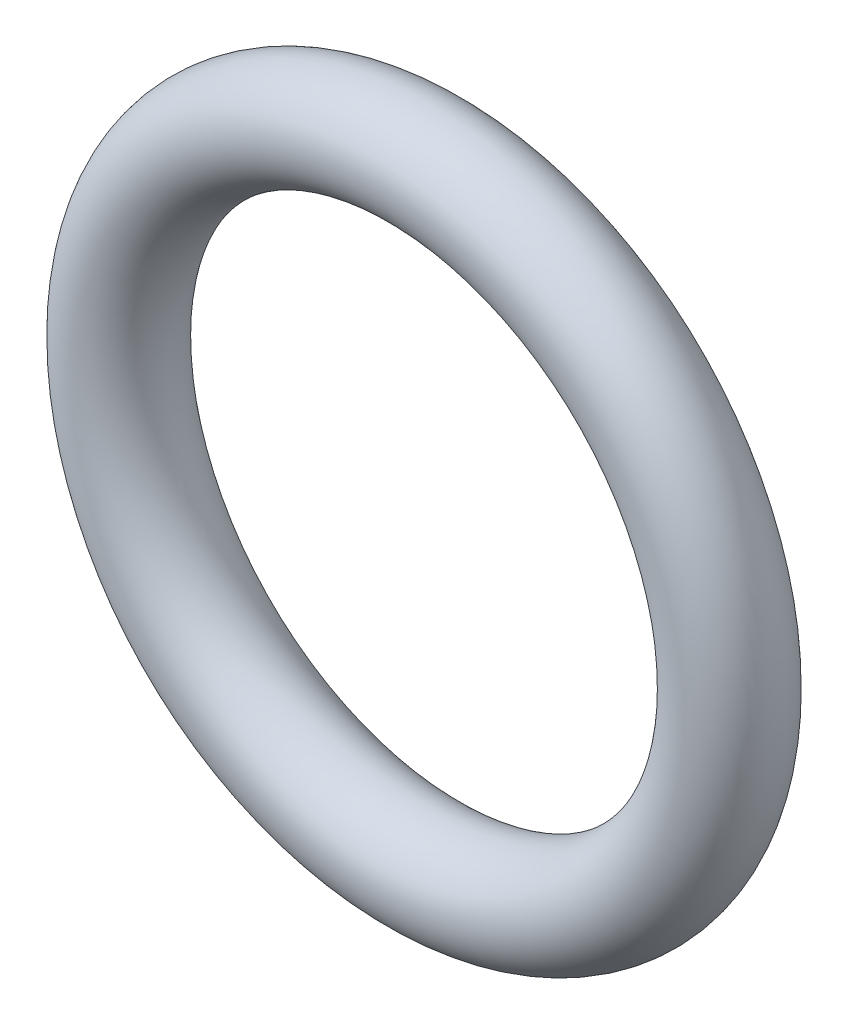
SolidWorks part; units mm, degrees
ref_plane "Przednia" through (0, 0, 0) normal (0, 0, 1) x (1, 0, 0)
ref_plane "Górna" through (0, 0, 0) normal (0, 1, 0) x (1, 0, 0)
ref_plane "Prawa" through (0, 0, 0) normal (1, 0, 0) x (0, 0, -1)
sketch "Szkic1" plane through (0, 0, 0) normal (0, 0, 1) x (1, 0, 0)
  circle A2 centre (0, 0) radius 6
  dimension "D3" = 12
sweep "Wyciągnięcie po ścieżce1" add path "Szkic1" circular profile diameter 2 parameters "D3"=2
